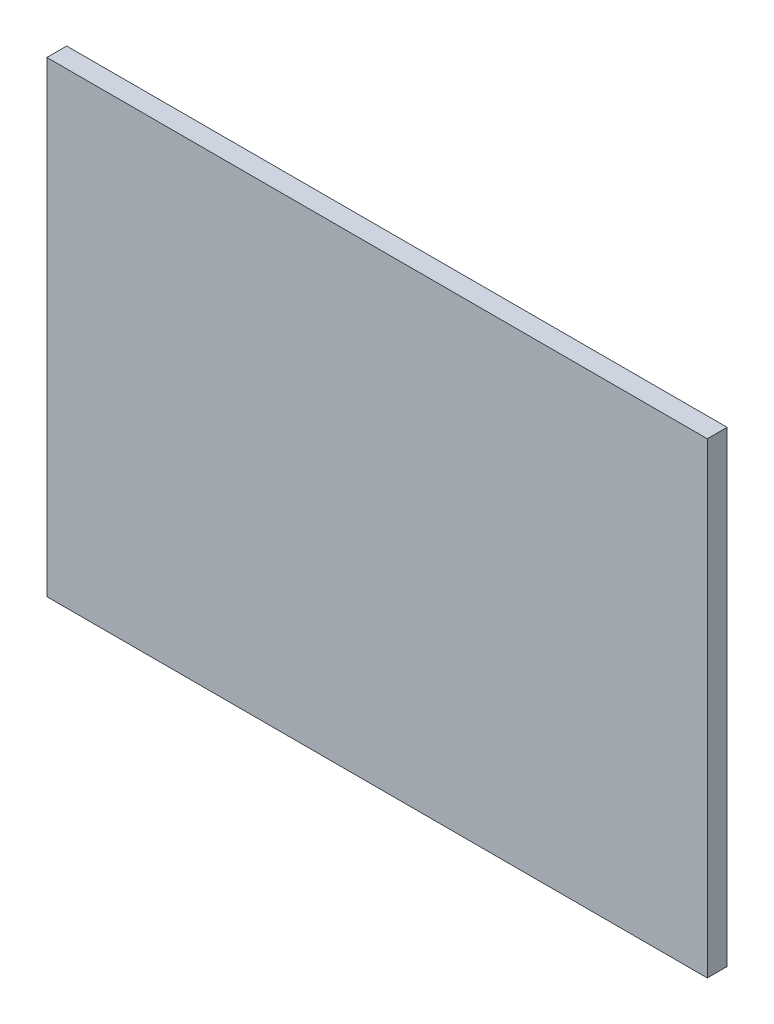
SolidWorks part; units mm, degrees
ref_plane "Front Plane" through (0, 0, 0) normal (0, 0, 1) x (1, 0, 0)
ref_plane "Top Plane" through (0, 0, 0) normal (0, 1, 0) x (1, 0, 0)
ref_plane "Right Plane" through (0, 0, 0) normal (1, 0, 0) x (0, 0, -1)
sketch "Sketch1" plane through (0, 0, 0) normal (0, 0, 1) x (1, 0, 0)
  line L1 (15, 110.7071) -> (115, 110.7071)
  line L2 (15, 110.7071) -> (15, 40)
  line L3 (15, 40) -> (115, 40)
  line L4 (115, 110.7071) -> (115, 40)
  dimension "D1" = 70.7071
  dimension "D2" = 100
extrude "Boss-Extrude1" add sketch "Sketch1" along normal blind 3
